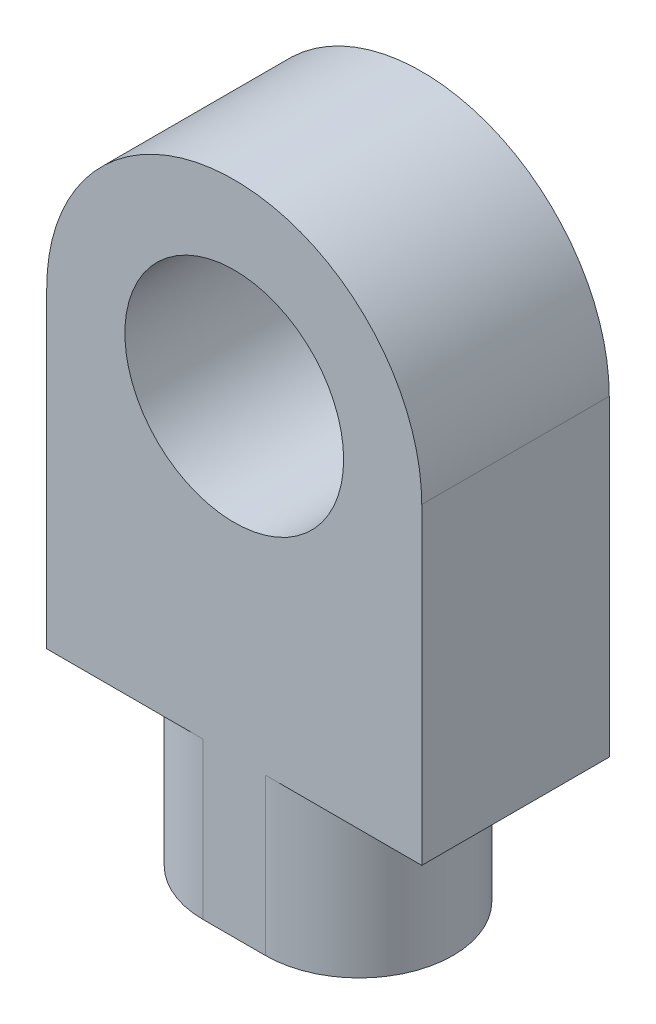
SolidWorks part; units mm, degrees
material "1060 Alloy"
ref_plane "Front Plane" through (0, 0, 0) normal (0, 0, 1) x (1, 0, 0)
ref_plane "Top Plane" through (0, 0, 0) normal (0, 1, 0) x (1, 0, 0)
ref_plane "Right Plane" through (0, 0, 0) normal (1, 0, 0) x (0, 0, -1)
sketch "Sketch1" plane through (0, 0, 0) normal (0, 0, 1) x (1, 0, 0)
  line L1 (-4, -5) -> (4, -5)
  line L2 (-4, -5) -> (-4, 0)
  line L4 (4, -5) -> (4, 0)
  line L6 (55, 0) -> (-55, 0) construction
  line L7 (-6, 0) -> (-4, 0)
  line L8 (-6, 0) -> (-6, 10)
  line L10 (6, 0) -> (6, 10)
  line L11 (4, 0) -> (6, 0)
  line L12 (0, -44.7868) -> (0, 44.7868) construction
  arc A0 (6, 10) -> (-6, 10) centre (0, 10) ccw
  dimension "D3" = 6
  dimension "D1" = 5
  dimension "D2" = 8
  dimension "D4" = 10
extrude "Boss-Extrude1" add sketch "Sketch1" along normal blind 6
hole_wizard "M8x1.0 Tapped Hole1" positions "Sketch2" profile "Sketch3" tap size "M8x1.0" standard "ISO"
sketch "Sketch2" plane through (0, 0, 6) normal (0, 0, 1) x (1, 0, 0)
  point P0 (0, 10)
sketch "Sketch3" plane through (0, 10, 6) normal (1, 0, 0) x (0, -1, 0)
  line L0 (0, 0) -> (0, 21.103)
  line L1 (0, 21.103) -> (3.5, 19)
  line L2 (3.5, 19) -> (3.5, 0)
  line L5 (3.5, 0) -> (0, 0)
  line L10 (0, 21.103) -> (-3.5, 19) construction
  line L11 (0, -6.35) -> (0, 107.95) construction
  dimension "Tap Drill Dia." = 7
  dimension "Tap Drill Depth" = 19
  dimension "Drill Angle" = 118
cosmetic thread "Hole Thread1" parameters "D1"=6, "D2"=8
sketch "Sketch4" plane through (0, -5, 0) normal (0, -1, 0) x (1, 0, 0)
  line L1 (-1, 6) -> (1, 6)
  line L3 (-1, 0) -> (1, 0)
  line L7 (-4.6031, 6.3752) -> (4.8273, 6.3752)
  line L8 (-4.6031, 6.3752) -> (-4.6031, -0.4898)
  line L9 (-4.6031, -0.4898) -> (4.8273, -0.4898)
  line L10 (4.8273, 6.3752) -> (4.8273, -0.4898)
  arc A0 (-1, 6) -> (-1, 0) centre (-1, 3) ccw
  arc A2 (1, 0) -> (1, 6) centre (1, 3) ccw
extrude "Cut-Extrude1" cut sketch "Sketch4" against normal up to surface (5 mm away) and the other way through all up to face at (-5, 0, 3)
